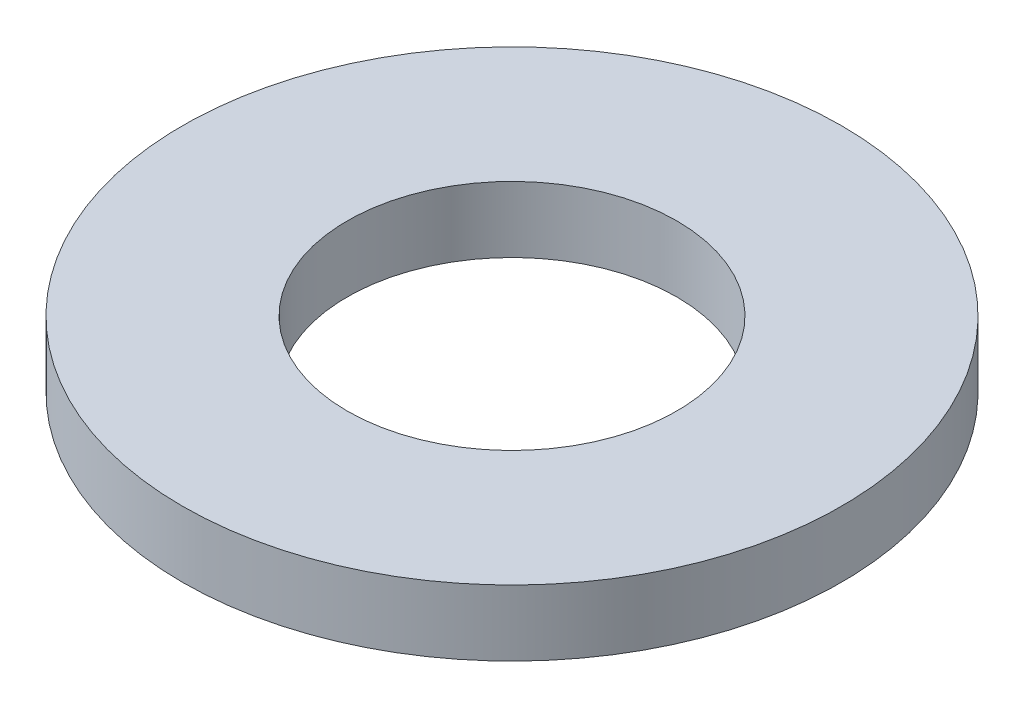
SolidWorks part; units mm, degrees
ref_plane "Front Plane" through (0, 0, 0) normal (0, 0, 1) x (1, 0, 0)
ref_plane "Top Plane" through (0, 0, 0) normal (0, 1, 0) x (1, 0, 0)
ref_plane "Right Plane" through (0, 0, 0) normal (1, 0, 0) x (0, 0, -1)
sketch "BodySke" plane through (0, 0, 0) normal (0, 0, -1) x (1, 0, 0)
  line L0 (0, 0) -> (0, 7.8986) construction
  line L2 (2, 0.8) -> (4, 0.8)
  line L3 (2, 0.8) -> (2, 0)
  line L4 (2, 0) -> (4, 0)
  line L5 (4, 0.8) -> (4, 0)
  dimension "Inner_dia" = 4
  dimension "Outer_dia" = 8
  dimension "Thickness" = 0.8
revolve "BaseBody" add sketch "BodySke" angle 360 about L0
